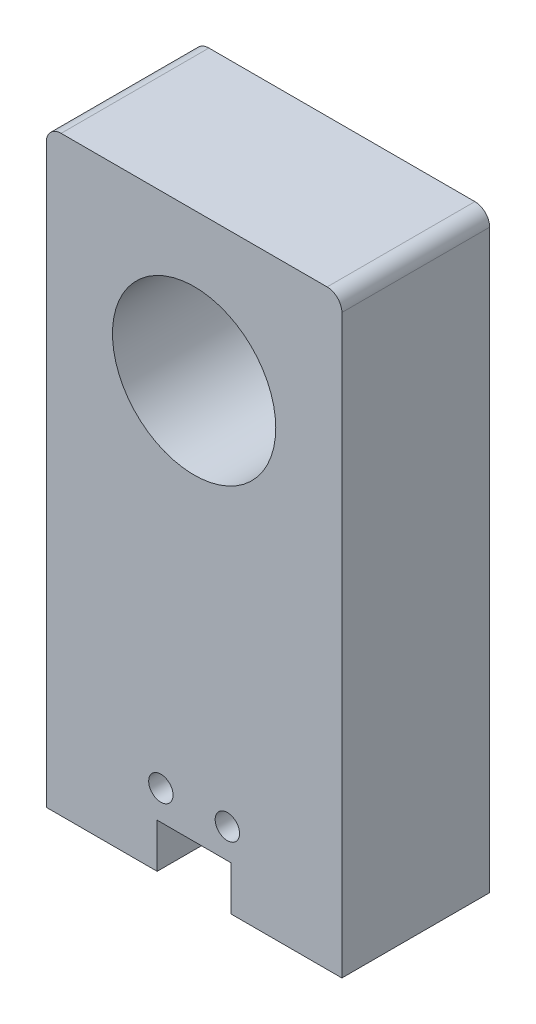
SolidWorks part; units mm, degrees
ref_plane "前视基准面" through (0, 0, 0) normal (0, 0, 1) x (1, 0, 0)
ref_plane "上视基准面" through (0, 0, 0) normal (0, 1, 0) x (1, 0, 0)
ref_plane "右视基准面" through (0, 0, 0) normal (1, 0, 0) x (0, 0, -1)
sketch "草图1" plane through (0, 0, 0) normal (0, 0, 1) x (1, 0, 0)
  line L1 (-20, -20) -> (20, -20)
  line L2 (-20, -20) -> (-20, 20)
  line L3 (-20, 20) -> (20, 20)
  line L4 (20, -20) -> (20, 20)
  line L5 (-20, -20) -> (20, 20) construction
  line L6 (-20, 20) -> (20, -20) construction
  point P0 (0, 0)
  dimension "D1" = 40
  dimension "D2" = 40
extrude "凸台-拉伸1" add sketch "草图1" along normal blind 20
sketch "草图2" plane through (0, 0, 20) normal (0, 0, 1) x (1, 0, 0)
  circle A0 centre (0, 0) radius 11.05
  dimension "D1" = 22.1
  dimension "D2" = 0
extrude "切除-拉伸1" cut sketch "草图2" against normal blind 20
sketch "草图3" plane through (0, -20, 0) normal (0, -1, 0) x (1, 0, 0)
  line L1 (-20, 0) -> (20, 0)
  line L2 (-20, 0) -> (-20, 20)
  line L3 (-20, 20) -> (20, 20)
  line L4 (20, 0) -> (20, 20)
  line L5 (-20, 0) -> (20, 20) construction
  line L6 (-20, 20) -> (20, 0) construction
  point P0 (0, 10)
extrude "凸台-拉伸2" add sketch "草图3" along normal blind 40
sketch "草图4" plane through (0, 0, 20) normal (0, 0, 1) x (1, 0, 0)
  line L0 (20, -60) -> (-20, -60) construction
  line L2 (0, 24.4829) -> (0, -73.983) construction
  circle A0 centre (4.5, -50) radius 1.65
  circle A1 centre (-4.5, -50) radius 1.65
  dimension "D1" = 3.3
  dimension "D2" = 10
  dimension "D3" = 3.3
  dimension "D4" = 4.5
  dimension "D5" = 4.5
  dimension "D6" = 10
extrude "切除-拉伸2" cut sketch "草图4" against normal blind 40
sketch "草图5" plane through (0, -60, 0) normal (0, -1, 0) x (1, 0, 0)
  line L0 (0, 21.447) -> (0, -4.8794) construction
  line L2 (-5, 8) -> (5, 8)
  line L3 (-5, 8) -> (-5, 20)
  line L4 (-5, 20) -> (5, 20)
  line L5 (5, 8) -> (5, 20)
  line L6 (-5, 8) -> (5, 20) construction
  line L7 (-5, 20) -> (5, 8) construction
  line L9 (20, 20) -> (-20, 20) construction
  point P3 (0, 14)
  dimension "D1" = 12
  dimension "D2" = 10
  dimension "D3" = 6
extrude "切除-拉伸3" cut sketch "草图5" against normal blind 6
fillet "圆角1" radius 2 2 edges at (20, 20, 10) (-20, 20, 10)
